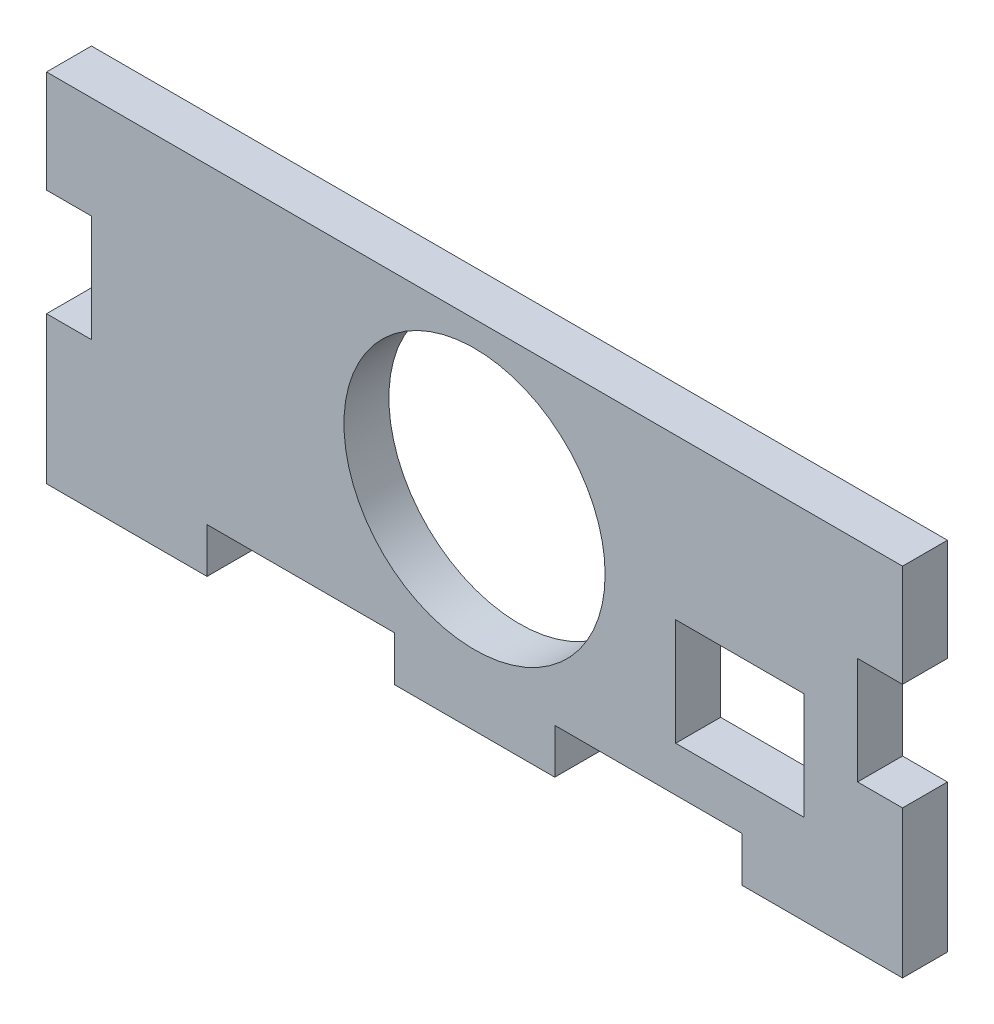
SolidWorks part; units mm, degrees
ref_plane "Front Plane" through (0, 0, 0) normal (0, 0, 1) x (1, 0, 0)
ref_plane "Top Plane" through (0, 0, 0) normal (0, 1, 0) x (1, 0, 0)
ref_plane "Right Plane" through (0, 0, 0) normal (1, 0, 0) x (0, 0, -1)
sketch "Sketch1" plane through (0, 0, 0) normal (0, 0, 1) x (1, 0, 0)
  line L1 (-50.8, 18.5) -> (50.8, 18.5)
  line L2 (-50.8, 18.5) -> (-50.8, -18.5)
  line L3 (-50.8, -18.5) -> (50.8, -18.5)
  line L4 (50.8, 18.5) -> (50.8, -18.5)
  line L5 (-50.8, 18.5) -> (50.8, -18.5) construction
  line L6 (-50.8, -18.5) -> (50.8, 18.5) construction
  point P0 (0, 0)
  dimension "D1" = 37
  dimension "D2" = 101.6
extrude "Boss-Extrude1" add sketch "Sketch1" against normal blind 5.334
sketch "Sketch2" plane through (0, 0, 0) normal (0, 0, 1) x (1, 0, 0)
  circle A0 centre (0, 0) radius 15.5
  dimension "D1" = 31
extrude "Motor Hole" cut sketch "Sketch2" against normal through all
sketch "Sketch4" plane through (0, -18.5, 0) normal (0, -1, 0) x (1, 0, 0)
  line L1 (0, 0) -> (0, -50000) construction
  line L2 (-50.8, -5.334) -> (50.8, -5.334) construction
  line L3 (-50.8, 0) -> (-31.75, 0)
  line L4 (-50.8, 0) -> (-50.8, -5.334)
  line L5 (-50.8, -5.334) -> (-31.75, -5.334)
  line L6 (-31.75, 0) -> (-31.75, -5.334)
  line L7 (-50.8, 0) -> (50.8, 0) construction
  line L8 (-9.525, 0) -> (9.525, 0)
  line L9 (-9.525, 0) -> (-9.525, -5.334)
  line L10 (-9.525, -5.334) -> (9.525, -5.334)
  line L11 (9.525, 0) -> (9.525, -5.334)
  line L12 (31.75, 0) -> (31.75, -5.334)
  line L13 (50.8, -5.334) -> (31.75, -5.334)
  line L14 (50.8, 0) -> (50.8, -5.334)
  line L15 (50.8, 0) -> (31.75, 0)
  dimension "D1" = 19.05
extrude "Bottom Tabs" add sketch "Sketch4" along normal blind 5.334
sketch "Sketch5" plane through (0, 0, 0) normal (0, 0, 1) x (1, 0, 0)
  line L0 (-50.8, 18.5) -> (-50.8, -23.834) construction
  line L1 (-50.8, 6.35) -> (-45.466, 6.35)
  line L2 (-50.8, 6.35) -> (-50.8, -6.35)
  line L3 (-50.8, -6.35) -> (-45.466, -6.35)
  line L4 (-45.466, 6.35) -> (-45.466, -6.35)
  line L5 (0, 0) -> (0, 50000) construction
  line L6 (0, 0) -> (-50000, 0) construction
  line L7 (45.466, 6.35) -> (45.466, -6.35)
  line L8 (50.8, -6.35) -> (45.466, -6.35)
  line L9 (50.8, 6.35) -> (50.8, -6.35)
  line L10 (50.8, 6.35) -> (45.466, 6.35)
  dimension "D1" = 12.7
  dimension "D2" = 5.334
extrude "Cut-Extrude1" cut sketch "Sketch5" against normal through all
extrude "Cut-Extrude2" cut sketch "Sketch6" against normal through all
sketch "Sketch6" plane through (16.2431, -7.1065, 20.4638) normal (0, 0, 1) x (1, 0, 0)
  line L1 (7.6329, 6.6405) -> (22.8729, 6.6405)
  line L2 (7.6329, 6.6405) -> (7.6329, -6.0595)
  line L3 (7.6329, -6.0595) -> (22.8729, -6.0595)
  line L4 (22.8729, 6.6405) -> (22.8729, -6.0595)
equation "\"material\"= \"gmaterial@base.assembly\""
equation "\"D1@Boss-Extrude1\"=\"material\""
equation "\"D1@Bottom Tabs\" = \"material\""
equation "\"D2@Sketch5\"=\"material\""
